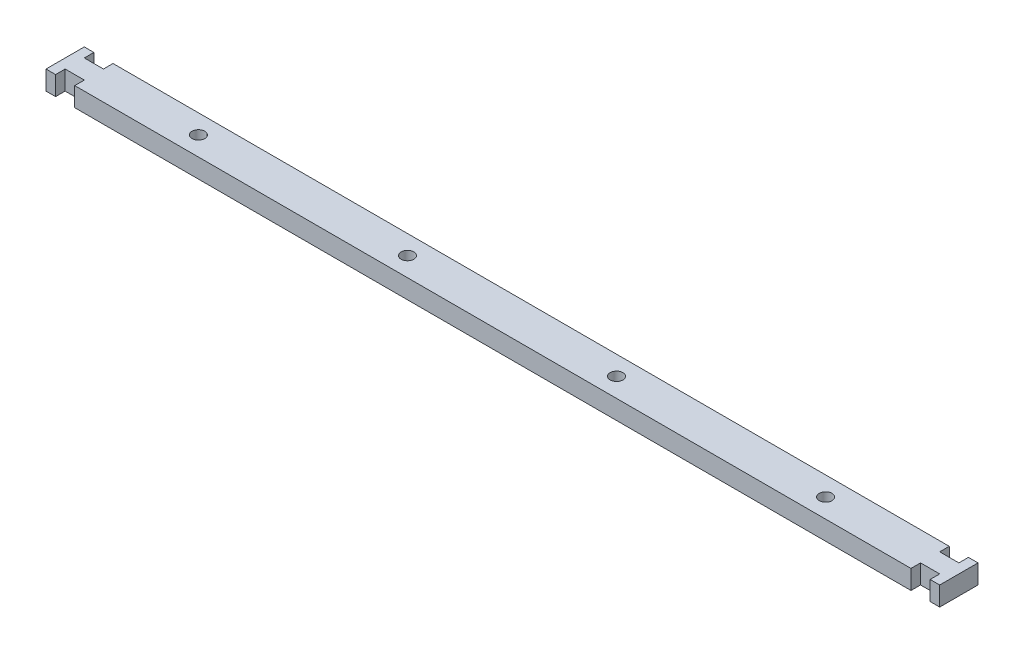
SolidWorks part; units mm, degrees
ref_plane "Front" through (0, 0, 0) normal (0, 0, 1) x (1, 0, 0)
ref_plane "Top" through (0, 0, 0) normal (0, 1, 0) x (1, 0, 0)
ref_plane "Right" through (0, 0, 0) normal (1, 0, 0) x (0, 0, -1)
sketch "Sketch1" plane through (0, 0, 0) normal (0, 1, 0) x (1, 0, 0)
  line L1 (-68.5, 3) -> (68.5, 3)
  line L2 (-68.5, 3) -> (-68.5, -3)
  line L3 (-68.5, -3) -> (68.5, -3)
  line L4 (68.5, 3) -> (68.5, -3)
  line L5 (-68.5, 3) -> (68.5, -3) construction
  line L6 (-68.5, -3) -> (68.5, 3) construction
  point P0 (0, 0)
  dimension "D1" = 6
  dimension "D2" = 137
extrude "Boss-Extrude1" add sketch "Sketch1" along normal blind 3
sketch "Sketch2" plane through (0, 3, 0) normal (0, 1, 0) x (1, 0, 0)
  line L0 (68.5, 3) -> (68.5, 1.5)
  line L1 (68.5, -3) -> (68.5, 3) construction
  line L2 (68.5, 1.5) -> (65.5, 1.5)
  line L3 (65.5, 1.5) -> (65.5, 3)
  line L4 (68.5, 3) -> (-68.5, 3) construction
  line L5 (65.5, 3) -> (68.5, 3)
  dimension "D1" = 1.5
  dimension "D2" = 3
extrude "Cut-Extrude1" cut sketch "Sketch2" against normal blind 3
mirror "Mirror1" about plane through (0, 0, 0) normal (0, 0, 1) of "Cut-Extrude1"
mirror "Mirror2" about plane through (0, 0, 0) normal (1, 0, 0) of "Mirror1", "Cut-Extrude1"
sketch "Sketch3" plane through (0, 3, 0) normal (0, 1, 0) x (1, 0, 0)
  line L0 (65.5, 3) -> (73.7234, 3)
  line L1 (65.5, -3) -> (73.7234, -3)
  line L7 (68.5, 1.5) -> (68.5, 3)
  line L8 (68.5, 3) -> (70, 3)
  line L9 (70, 3) -> (70, -3)
  line L10 (70, -3) -> (68.5, -3)
  line L11 (68.5, -3) -> (68.5, 3)
  line M14 (68.5, -1.5) -> (68.5, 1.5)
  dimension "D1" = 1.5
extrude "Boss-Extrude2" add sketch "Sketch3" against normal blind 3 contours L11 L1 L9 L0 L7 M14
mirror "Mirror3" about plane through (0, 0, 0) normal (1, 0, 0) of "Boss-Extrude2"
sketch "Sketch4" plane through (0, 3, 0) normal (0, 1, 0) x (1, 0, 0)
  line L0 (-65.5, -1.5) -> (-65.5, 1.5)
  line L2 (-65.5, 1.5) -> (-65.5, 0)
  line L3 (-65.5, 0) -> (0, 0)
  line L4 (0, 0) -> (-32.75, 0)
  line L5 (-32.75, 0) -> (-65.5, 0)
  line L6 (-32.75, 0) -> (0, 0)
  circle A1 centre (-49.125, 0) radius 1
  circle A2 centre (-16.375, 0) radius 1
  dimension "D1" = 2
  dimension "D2" = 2
extrude "Cut-Extrude2" cut sketch "Sketch4" against normal blind 3 contours L5 A1 | L6 A2 | L6 A2
mirror "Mirror4" about plane through (0, 0, 0) normal (1, 0, 0) of "Cut-Extrude2"
